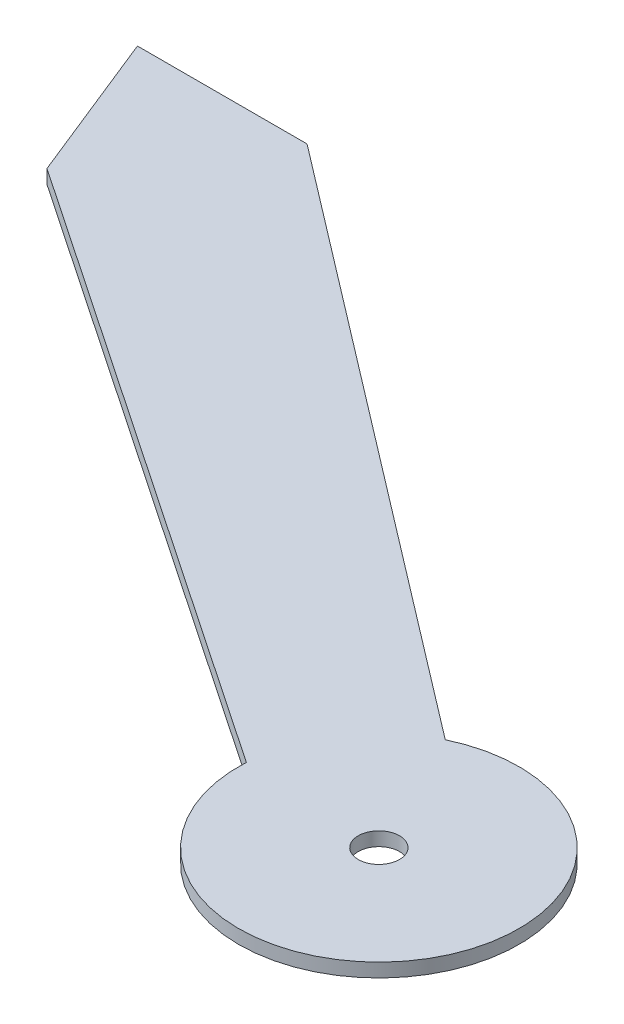
SolidWorks part; units mm, degrees
ref_plane "Front Plane" through (0, 0, 0) normal (0, 0, 1) x (1, 0, 0)
ref_plane "Top Plane" through (0, 0, 0) normal (0, 1, 0) x (1, 0, 0)
ref_plane "Right Plane" through (0, 0, 0) normal (1, 0, 0) x (0, 0, -1)
sketch "Sketch1" plane through (0, 0, 0) normal (0, 1, 0) x (1, 0, 0)
  line L1 (-5.929, 4.1725) -> (-5.4862, 3.0714)
  line L2 (-5.4862, 3.0714) -> (-1.019, 0.055)
  line L3 (-5.929, 4.1725) -> (-4.695, 4.1725)
  line L4 (-4.695, 4.1725) -> (-0.4385, 0.9215)
  line L5 (-5.4862, 3.8609) -> (-5.2169, 3.2715)
  line L6 (-5.2169, 3.2715) -> (-2.2002, 1.2399)
  line L7 (-2.2002, 1.2399) -> (-1.9486, 1.6135)
  line L8 (-1.9486, 1.6135) -> (-4.891, 3.8609)
  line L9 (-4.891, 3.8609) -> (-5.4862, 3.8609)
  arc A0 (-1.019, 0.055) -> (-0.4385, 0.9215) centre (0, 0) ccw
  circle A2 centre (0, 0) radius 0.15
  dimension "D1" = 0.3
extrude "Boss-Extrude1" add sketch "Sketch1" along normal blind 0.1
sketch "Sketch3" plane through (0, 0.1, 0) normal (0, 1, 0) x (1, 0, 0)
  line L0 (-5.6698, 4.0608) -> (-4.6073, 3.9522)
  line L1 (-4.6073, 3.9522) -> (-1.5516, 1.5294)
  line L2 (-1.5516, 1.5294) -> (-2.045, 0.9806)
  line L3 (-2.045, 0.9806) -> (-5.3884, 3.17)
  line L4 (-5.3884, 3.17) -> (-5.6698, 4.0608)
extrude "Boss-Extrude3" add sketch "Sketch3" against normal blind 0.02
